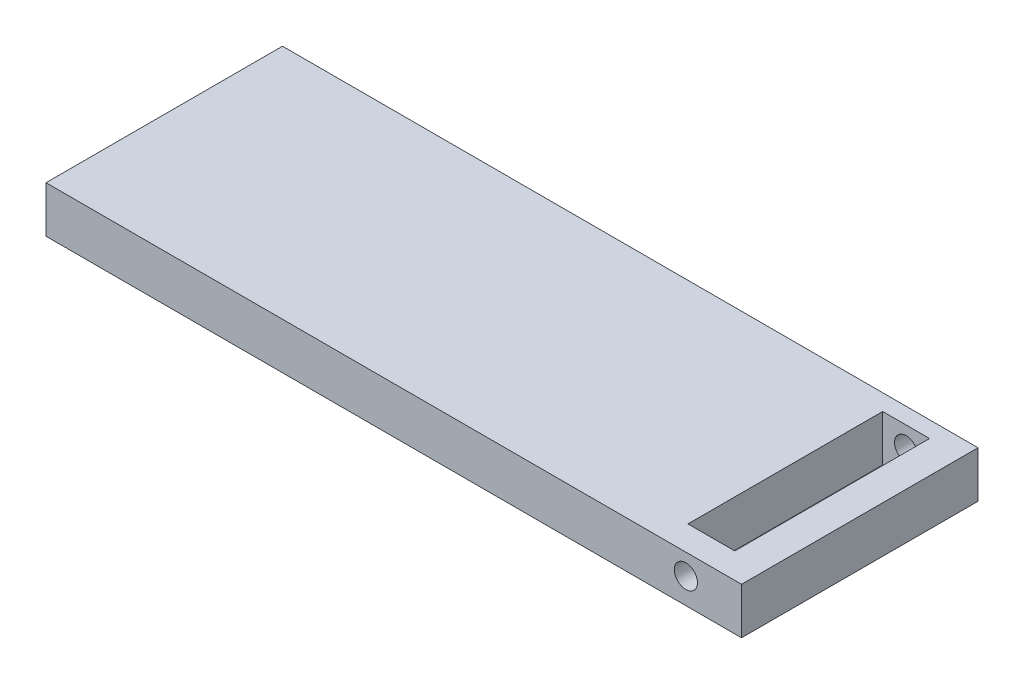
SolidWorks part; units mm, degrees
material "Balsa"
ref_plane "Plan de face" through (0, 0, 0) normal (0, 0, 1) x (1, 0, 0)
ref_plane "Plan de dessus" through (0, 0, 0) normal (0, 1, 0) x (1, 0, 0)
ref_plane "Plan de droite" through (0, 0, 0) normal (1, 0, 0) x (0, 0, -1)
sketch "Sketch1" plane through (0, 0, 0) normal (0, 1, 0) x (1, 0, 0)
  line L1 (-75, -25.5) -> (75, -25.5)
  line L2 (-75, -25.5) -> (-75, 25.5)
  line L3 (-75, 25.5) -> (75, 25.5)
  line L4 (75, -25.5) -> (75, 25.5)
  line L5 (-75, -25.5) -> (75, 25.5) construction
  line L6 (-75, 25.5) -> (75, -25.5) construction
  point P0 (0, 0)
  dimension "D1" = 51
  dimension "D2" = 150
extrude "Boss-Extrude1" add sketch "Sketch1" along normal blind 10
sketch "Sketch2" plane through (0, 10, 0) normal (0, 1, 0) x (1, 0, 0)
  line L0 (-75, -25.5) -> (75, -25.5) construction
  line L1 (57.95, -20) -> (68.05, -20)
  line L2 (57.95, -20) -> (57.95, 22)
  line L3 (57.95, 22) -> (68.05, 22)
  line L4 (68.05, -20) -> (68.05, 22)
  line L5 (57.95, -20) -> (68.05, 22) construction
  line L6 (57.95, 22) -> (68.05, -20) construction
  line L8 (75, -25.5) -> (75, 25.5) construction
  point P0 (63, 1)
  dimension "D1" = 10.1
  dimension "D2" = 42
  dimension "D3" = 5.5
  dimension "D4" = 12
extrude "Cut-Extrude1" cut sketch "Sketch2" against normal through all
sketch "Sketch5" plane through (0, 0, 25.5) normal (0, 0, 1) x (1, 0, 0)
  line L0 (75, 10) -> (75, 0) construction
  circle A0 centre (63, 5.5156) radius 2.5
  dimension "D2" = 5
  dimension "D1" = 12
extrude "Cut-Extrude4" cut sketch "Sketch5" against normal through all
